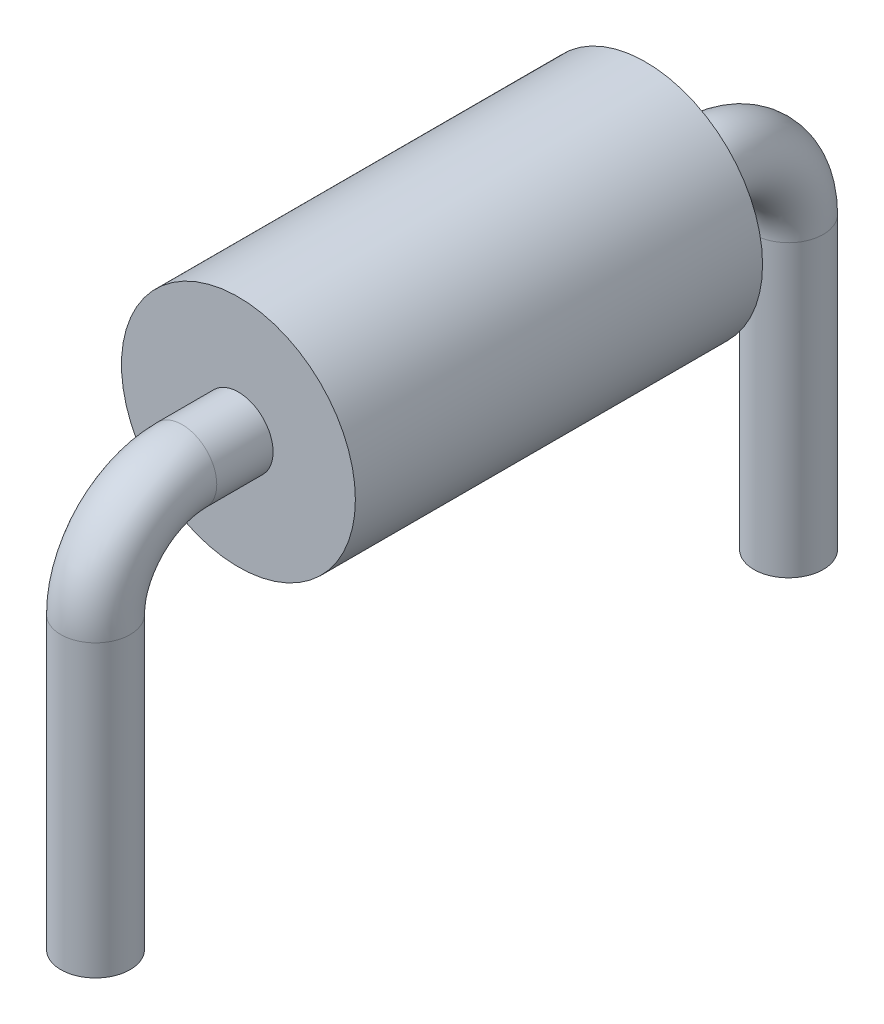
SolidWorks part; units mm, degrees
ref_plane "Спереди" through (0, 0, 0) normal (0, 0, 1) x (1, 0, 0)
ref_plane "Сверху" through (0, 0, 0) normal (0, 1, 0) x (1, 0, 0)
ref_plane "Справа" through (0, 0, 0) normal (1, 0, 0) x (0, 0, -1)
sketch "Эскиз1" plane through (0, 0, 0) normal (0, 0, 1) x (1, 0, 0)
  circle A0 centre (0, 0) radius 1.35
extrude "Бобышка-Вытянуть1" add sketch "Эскиз1" along normal mid plane 4.7
sketch "Эскиз2" plane through (0, 0, 2.35) normal (0, 0, 1) x (1, 0, 0)
  circle A0 centre (0, 0) radius 0.4
sketch "Эскиз3" plane through (0, 0, -2.35) normal (0, 0, -1) x (-1, 0, 0)
  circle A0 centre (0, 0) radius 0.4
sketch "Эскиз5" plane through (0, 0, 0) normal (1, 0, 0) x (0, 0, -1)
  line L0 (0, 0) -> (3, 0)
  line L1 (4, -1) -> (4, -4.35)
  line L2 (-2.35, -1.35) -> (2.35, -1.35) construction
  arc A0 (3, 0) -> (4, -1) centre (3, -1) cw
  point P6 (0, 0)
  point P7 (0, 0)
  dimension "D2" = 1
  dimension "D1" = 4
  dimension "D3" = 3
sweep "По траектории1" add profiles "Эскиз3" path "Эскиз5"
sketch "Эскиз6" plane through (0, 0, 0) normal (1, 0, 0) x (0, 0, -1)
  line L0 (0, 0) -> (-3, 0)
  line L1 (-4, -1) -> (-4, -4.35)
  arc A0 (-4, -1) -> (-3, 0) centre (-3, -1) cw
  point P6 (0, 0)
  point P7 (0, 0)
  dimension "D3" = 1
  dimension "D1" = 4
  dimension "D2" = 3
sweep "По траектории2" add profiles "Эскиз2" path "Эскиз6"
